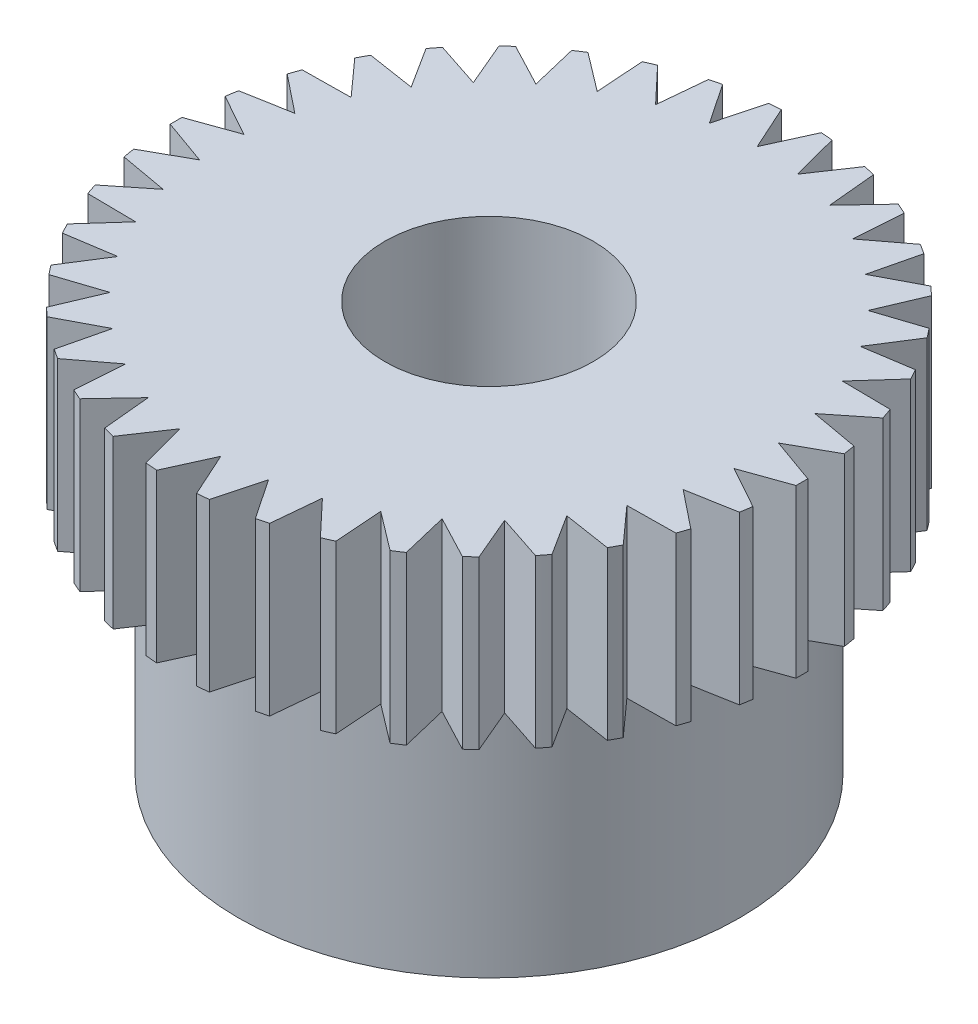
SolidWorks part; units mm, degrees
ref_plane "Спереди" through (0, 0, 0) normal (0, 0, 1) x (1, 0, 0)
ref_plane "Сверху" through (0, 0, 0) normal (0, 1, 0) x (1, 0, 0)
ref_plane "Справа" through (0, 0, 0) normal (1, 0, 0) x (0, 0, -1)
sketch "Эскиз1" plane through (0, 0, 0) normal (0, 1, 0) x (1, 0, 0)
  circle A0 centre (0, 0) radius 6
extrude "Вытянуть1" add sketch "Эскиз1" along normal blind 5.8
sketch "Эскиз2" plane through (0, 5.8, 0) normal (0, 1, 0) x (1, 0, 0)
  line L0 (0, 7.5) -> (0, 6.3301) construction
  circle A0 centre (0, 0) radius 7.5
  point P10 (0, 7.642)
extrude "Вытянуть2" add sketch "Эскиз2" along normal blind 4
sketch "Эскиз3" plane through (0, 9.8, 0) normal (0, 1, 0) x (1, 0, 0)
  line L0 (0, 7.5) -> (0, 5.3856) construction
  line L1 (-0.6228, 7.8025) -> (0.6228, 7.8025)
  line L2 (0.6228, 7.8025) -> (0, 6.4283)
  line L3 (-0.6228, 7.8025) -> (0, 6.4283)
  line L4 (0.67, 7.7986) -> (1.8986, 7.5936)
  line L5 (0.67, 7.7986) -> (1.0581, 6.3407)
  line L6 (1.8986, 7.5936) -> (1.0581, 6.3407)
  line L7 (1.9444, 7.582) -> (3.1225, 7.1776)
  line L8 (1.9444, 7.582) -> (2.0873, 6.08)
  line L9 (3.1225, 7.1776) -> (2.0873, 6.08)
  line L10 (3.1659, 7.1585) -> (4.2613, 6.5657)
  line L11 (3.1659, 7.1585) -> (3.0596, 5.6536)
  line L12 (4.2613, 6.5657) -> (3.0596, 5.6536)
  line L13 (4.301, 6.5398) -> (5.2839, 5.7748)
  line L14 (4.301, 6.5398) -> (3.9484, 5.0729)
  line L15 (5.2839, 5.7748) -> (3.9484, 5.0729)
  line L16 (5.3187, 5.7427) -> (6.1623, 4.8263)
  line L17 (5.3187, 5.7427) -> (4.7295, 4.3538)
  line L18 (6.1623, 4.8263) -> (4.7295, 4.3538)
  line L19 (6.1914, 4.789) -> (6.8727, 3.7462)
  line L20 (6.1914, 4.789) -> (5.3816, 3.516)
  line L21 (6.8727, 3.7462) -> (5.3816, 3.516)
  line L22 (6.8952, 3.7046) -> (7.3955, 2.5639)
  line L23 (6.8952, 3.7046) -> (5.8869, 2.5822)
  line L24 (7.3955, 2.5639) -> (5.8869, 2.5822)
  line L25 (7.4109, 2.5191) -> (7.7167, 1.3117)
  line L26 (7.4109, 2.5191) -> (6.2316, 1.5781)
  line L27 (7.7167, 1.3117) -> (6.2316, 1.5781)
  line L28 (7.7245, 1.265) -> (7.8273, 0.0237)
  line L29 (7.7245, 1.265) -> (6.4064, 0.5308)
  line L30 (7.8273, 0.0237) -> (6.4064, 0.5308)
  line L31 (7.8273, -0.0237) -> (7.7245, -1.265)
  line L32 (7.8273, -0.0237) -> (6.4064, -0.5308)
  line L33 (7.7245, -1.265) -> (6.4064, -0.5308)
  line L34 (7.7167, -1.3117) -> (7.4109, -2.5191)
  line L35 (7.7167, -1.3117) -> (6.2316, -1.5781)
  line L36 (7.4109, -2.5191) -> (6.2316, -1.5781)
  line L37 (7.3955, -2.5639) -> (6.8952, -3.7046)
  line L38 (7.3955, -2.5639) -> (5.8869, -2.5822)
  line L39 (6.8952, -3.7046) -> (5.8869, -2.5822)
  line L40 (6.8727, -3.7462) -> (6.1914, -4.789)
  line L41 (6.8727, -3.7462) -> (5.3816, -3.516)
  line L42 (6.1914, -4.789) -> (5.3816, -3.516)
  line L43 (6.1623, -4.8263) -> (5.3187, -5.7427)
  line L44 (6.1623, -4.8263) -> (4.7295, -4.3538)
  line L45 (5.3187, -5.7427) -> (4.7295, -4.3538)
  line L46 (5.2839, -5.7748) -> (4.301, -6.5398)
  line L47 (5.2839, -5.7748) -> (3.9484, -5.0729)
  line L48 (4.301, -6.5398) -> (3.9484, -5.0729)
  line L49 (4.2613, -6.5657) -> (3.1659, -7.1585)
  line L50 (4.2613, -6.5657) -> (3.0596, -5.6536)
  line L51 (3.1659, -7.1585) -> (3.0596, -5.6536)
  line L52 (3.1225, -7.1776) -> (1.9444, -7.582)
  line L53 (3.1225, -7.1776) -> (2.0873, -6.08)
  line L54 (1.9444, -7.582) -> (2.0873, -6.08)
  line L55 (1.8986, -7.5936) -> (0.67, -7.7986)
  line L56 (1.8986, -7.5936) -> (1.0581, -6.3407)
  line L57 (0.67, -7.7986) -> (1.0581, -6.3407)
  line L58 (0.6228, -7.8025) -> (-0.6228, -7.8025)
  line L59 (0.6228, -7.8025) -> (0, -6.4283)
  line L60 (-0.6228, -7.8025) -> (0, -6.4283)
  line L61 (-0.67, -7.7986) -> (-1.8986, -7.5936)
  line L62 (-0.67, -7.7986) -> (-1.0581, -6.3407)
  line L63 (-1.8986, -7.5936) -> (-1.0581, -6.3407)
  line L64 (-1.9444, -7.582) -> (-3.1225, -7.1776)
  line L65 (-1.9444, -7.582) -> (-2.0873, -6.08)
  line L66 (-3.1225, -7.1776) -> (-2.0873, -6.08)
  line L67 (-3.1659, -7.1585) -> (-4.2613, -6.5657)
  line L68 (-3.1659, -7.1585) -> (-3.0596, -5.6536)
  line L69 (-4.2613, -6.5657) -> (-3.0596, -5.6536)
  line L70 (-4.301, -6.5398) -> (-5.2839, -5.7748)
  line L71 (-4.301, -6.5398) -> (-3.9484, -5.0729)
  line L72 (-5.2839, -5.7748) -> (-3.9484, -5.0729)
  line L73 (-5.3187, -5.7427) -> (-6.1623, -4.8263)
  line L74 (-5.3187, -5.7427) -> (-4.7295, -4.3538)
  line L75 (-6.1623, -4.8263) -> (-4.7295, -4.3538)
  line L76 (-6.1914, -4.789) -> (-6.8727, -3.7462)
  line L77 (-6.1914, -4.789) -> (-5.3816, -3.516)
  line L78 (-6.8727, -3.7462) -> (-5.3816, -3.516)
  line L79 (-6.8952, -3.7046) -> (-7.3955, -2.5639)
  line L80 (-6.8952, -3.7046) -> (-5.8869, -2.5822)
  line L81 (-7.3955, -2.5639) -> (-5.8869, -2.5822)
  line L82 (-7.4109, -2.5191) -> (-7.7167, -1.3117)
  line L83 (-7.4109, -2.5191) -> (-6.2316, -1.5781)
  line L84 (-7.7167, -1.3117) -> (-6.2316, -1.5781)
  line L85 (-7.7245, -1.265) -> (-7.8273, -0.0237)
  line L86 (-7.7245, -1.265) -> (-6.4064, -0.5308)
  line L87 (-7.8273, -0.0237) -> (-6.4064, -0.5308)
  line L88 (-7.8273, 0.0237) -> (-7.7245, 1.265)
  line L89 (-7.8273, 0.0237) -> (-6.4064, 0.5308)
  line L90 (-7.7245, 1.265) -> (-6.4064, 0.5308)
  line L91 (-7.7167, 1.3117) -> (-7.4109, 2.5191)
  line L92 (-7.7167, 1.3117) -> (-6.2316, 1.5781)
  line L93 (-7.4109, 2.5191) -> (-6.2316, 1.5781)
  line L94 (-7.3955, 2.5639) -> (-6.8952, 3.7046)
  line L95 (-7.3955, 2.5639) -> (-5.8869, 2.5822)
  line L96 (-6.8952, 3.7046) -> (-5.8869, 2.5822)
  line L97 (-6.8727, 3.7462) -> (-6.1914, 4.789)
  line L98 (-6.8727, 3.7462) -> (-5.3816, 3.516)
  line L99 (-6.1914, 4.789) -> (-5.3816, 3.516)
  line L100 (-6.1623, 4.8263) -> (-5.3187, 5.7427)
  line L101 (-6.1623, 4.8263) -> (-4.7295, 4.3538)
  line L102 (-5.3187, 5.7427) -> (-4.7295, 4.3538)
  line L103 (-5.2839, 5.7748) -> (-4.301, 6.5398)
  line L104 (-5.2839, 5.7748) -> (-3.9484, 5.0729)
  line L105 (-4.301, 6.5398) -> (-3.9484, 5.0729)
  line L106 (-4.2613, 6.5657) -> (-3.1659, 7.1585)
  line L107 (-4.2613, 6.5657) -> (-3.0596, 5.6536)
  line L108 (-3.1659, 7.1585) -> (-3.0596, 5.6536)
  line L109 (-3.1225, 7.1776) -> (-1.9444, 7.582)
  line L110 (-3.1225, 7.1776) -> (-2.0873, 6.08)
  line L111 (-1.9444, 7.582) -> (-2.0873, 6.08)
  line L112 (-1.8986, 7.5936) -> (-0.67, 7.7986)
  line L113 (-1.8986, 7.5936) -> (-1.0581, 6.3407)
  line L114 (-0.67, 7.7986) -> (-1.0581, 6.3407)
  point P8 (0, 7.8025)
extrude "Вытянуть3" cut sketch "Эскиз3" against normal through all
sketch "Эскиз4" plane through (0, 0, 0) normal (0, -1, 0) x (1, 0, 0)
  circle A0 centre (0, 0) radius 2.5
extrude "Вытянуть4" cut sketch "Эскиз4" against normal through all
